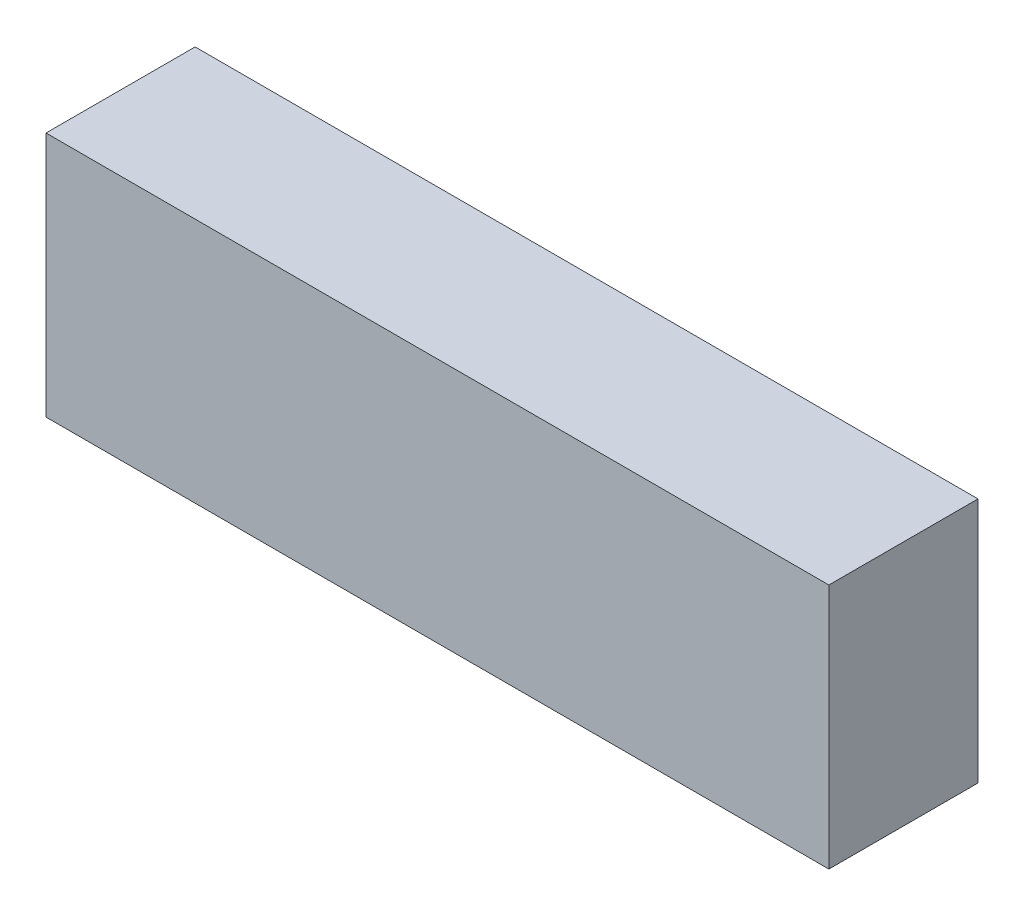
SolidWorks part; units mm, degrees
ref_plane "前视基准面" through (0, 0, 0) normal (0, 0, 1) x (1, 0, 0)
ref_plane "上视基准面" through (0, 0, 0) normal (0, 1, 0) x (1, 0, 0)
ref_plane "右视基准面" through (0, 0, 0) normal (1, 0, 0) x (0, 0, -1)
other "Configuration Table"
sketch "草图1" plane through (0, 0, 0) normal (0, 0, 1) x (1, 0, 0)
  line L1 (-44.2205, 5.7127) -> (60.7795, 5.7127)
  line L2 (-44.2205, 5.7127) -> (-44.2205, -27.2873)
  line L3 (-44.2205, -27.2873) -> (60.7795, -27.2873)
  line L4 (60.7795, 5.7127) -> (60.7795, -27.2873)
  dimension "D1" = 105
  dimension "D2" = 33
extrude "凸台-拉伸1" add sketch "草图1" along normal blind 20
